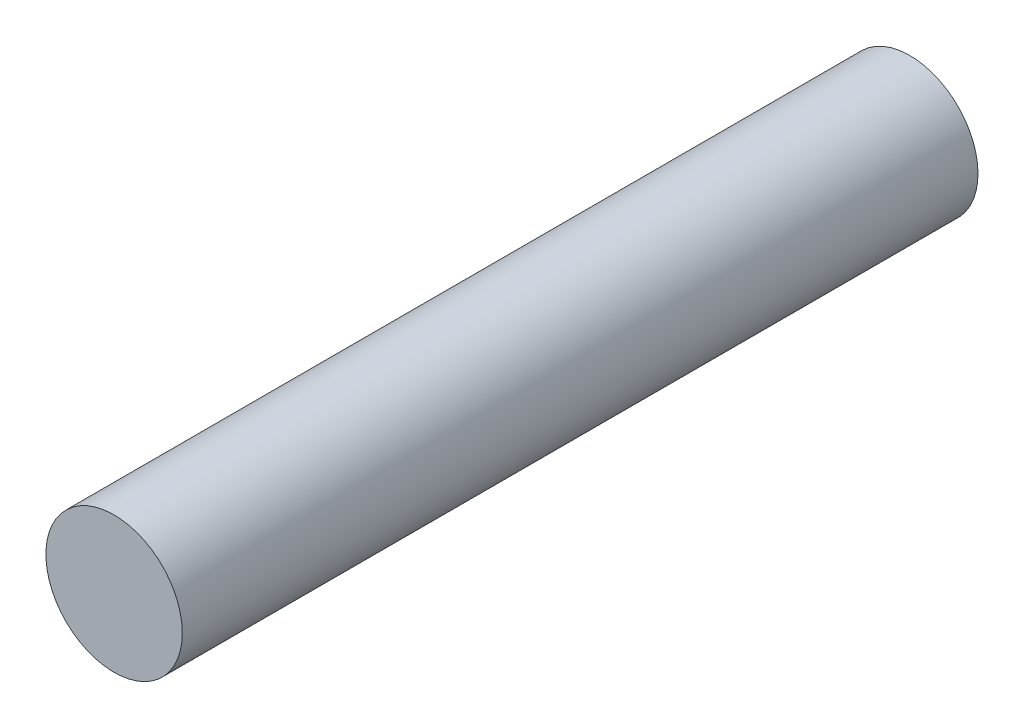
SolidWorks part; units mm, degrees
ref_plane "Front Plane" through (0, 0, 0) normal (0, 0, 1) x (1, 0, 0)
ref_plane "Top Plane" through (0, 0, 0) normal (0, 1, 0) x (1, 0, 0)
ref_plane "Right Plane" through (0, 0, 0) normal (1, 0, 0) x (0, 0, -1)
sketch "Sketch1" plane through (0, 0, 0) normal (0, 0, 1) x (1, 0, 0)
  circle A0 centre (0, 0) radius 3
  dimension "D1" = 6
extrude "Boss-Extrude1" add sketch "Sketch1" along normal blind 35
